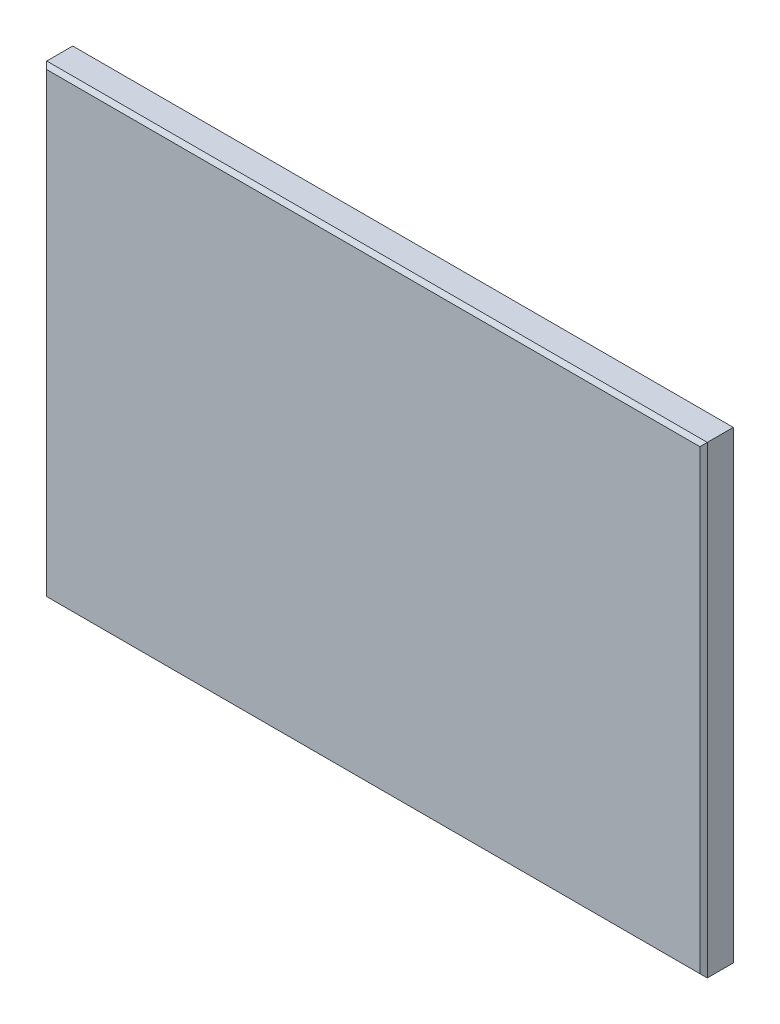
SolidWorks part; units mm, degrees
material "PF"
ref_plane "정면" through (0, 0, 0) normal (0, 0, 1) x (1, 0, 0)
ref_plane "윗면" through (0, 0, 0) normal (0, 1, 0) x (1, 0, 0)
ref_plane "우측면" through (0, 0, 0) normal (1, 0, 0) x (0, 0, -1)
sketch "스케치1" plane through (0, 0, 0) normal (0, 0, 1) x (1, 0, 0)
  line L1 (-178, 125) -> (178, 125)
  line L2 (-178, 125) -> (-178, -125)
  line L3 (-178, -125) -> (178, -125)
  line L4 (178, 125) -> (178, -125)
  dimension "D1" = 178
  dimension "D2" = 178
  dimension "D3" = 125
  dimension "D4" = 125
extrude "보스-돌출1" add sketch "스케치1" along normal blind 20
chamfer "모따기1" distance 4 angle 45 4 edges at (0, -125, 0) (178, 0, 0) (0, 125, 0) (-178, 0, 0)
chamfer "모따기2" distance 2 angle 45 4 edges at (0, 125, 20) (178, 0, 20) (0, -125, 20) (-178, 0, 20)
